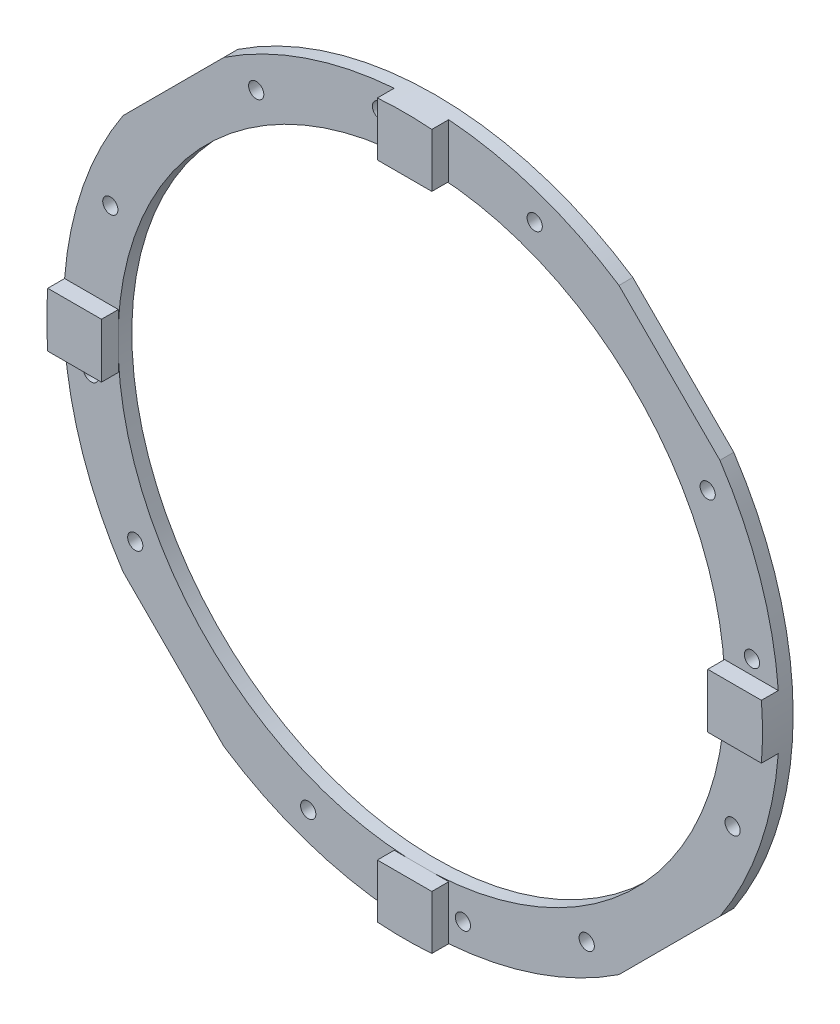
SolidWorks part; units mm, degrees
ref_plane "Front Plane" through (0, 0, 0) normal (0, 0, 1) x (1, 0, 0)
ref_plane "Top Plane" through (0, 0, 0) normal (0, 1, 0) x (1, 0, 0)
ref_plane "Right Plane" through (0, 0, 0) normal (1, 0, 0) x (0, 0, -1)
sketch "Sketch1" plane through (0, 0, 0) normal (0, 0, 1) x (1, 0, 0)
  line L0 (0, 284.5128) -> (0, -315.9314) construction
  line L1 (-464.297, 0) -> (544.589, 0) construction
  circle A2 centre (0, 0) radius 137.5
  circle A3 centre (0, 0) radius 109.75
  dimension "D2" = 275
  dimension "D3" = 219.5
sketch "Sketch2" plane through (0, 0, 0) normal (0, 0, 1) x (1, 0, 0)
  line L1 (0, 193.6178) -> (0, -181.834) construction
  line L2 (0, 284.5128) -> (0, -315.9314) construction
  line L3 (-312.5976, 0) -> (255.9939, 0) construction
  line L4 (-464.297, 0) -> (544.589, 0) construction
  line L5 (-61.2695, 129.5) -> (85.8777, 129.5) construction
  line L6 (-105.1774, 119.5) -> (123.1159, 119.5) construction
  line L7 (0, 0) -> (52.2887, 143.6619) construction
  circle A2 centre (0, 0) radius 109.725
  circle A3 centre (0, 0) radius 129.4
  circle A5 centre (-15, 119.5) radius 2.75
  circle A6 centre (40.9484, 112.5047) radius 2.75
  circle A7 centre (119.5, 15) radius 2.75
  circle A8 centre (112.5047, -40.9484) radius 2.75
  circle A9 centre (15, -119.5) radius 2.75
  circle A10 centre (-40.9484, -112.5047) radius 2.75
  circle A11 centre (-119.5, -15) radius 2.75
  circle A12 centre (-112.5047, 40.9484) radius 2.75
  point P1 (114.75, 0)
  point P3 (0, 0)
  point P9 (104.9544, 32.0878)
  dimension "D1" = 219.45
  dimension "D2" = 258.8
  dimension "D3" = 129.5
  dimension "D5" = 5.5
  dimension "D8" = 5.5
  dimension "D10" = 4
  dimension "D9" = 119.725
  dimension "D4" = 10
  dimension "D6" = 15
  dimension "D7" = 20
extrude "Boss-Extrude1" add sketch "Sketch2" along normal blind 5
sketch "Sketch3" plane through (0, 0, 5) normal (0, 0, 1) x (1, 0, 0)
  line L0 (0, 206.7973) -> (0, -176.6166) construction
  line L2 (-227.1373, 0) -> (214.6054, 0) construction
  line L3 (-464.297, 0) -> (544.589, 0) construction
  line L7 (0, 284.5128) -> (0, -315.9314) construction
  line L18 (-9.85, 129.0246) -> (-9.85, 109.6)
  line L19 (-9.85, 109.6) -> (9.85, 109.6)
  line L20 (9.85, 129.0246) -> (9.85, 109.6)
  line L21 (129.0246, 9.85) -> (109.6, 9.85)
  line L22 (109.6, 9.85) -> (109.6, -9.85)
  line L23 (129.0246, -9.85) -> (109.6, -9.85)
  line L24 (9.85, -129.0246) -> (9.85, -109.6)
  line L25 (9.85, -109.6) -> (-9.85, -109.6)
  line L26 (-9.85, -129.0246) -> (-9.85, -109.6)
  line L27 (-129.0246, -9.85) -> (-109.6, -9.85)
  line L28 (-109.6, -9.85) -> (-109.6, 9.85)
  line L29 (-129.0246, 9.85) -> (-109.6, 9.85)
  arc A8 (9.85, 129.0246) -> (-9.85, 129.0246) centre (0, 0) ccw
  arc A9 (129.0246, -9.85) -> (129.0246, 9.85) centre (0, 0) ccw
  arc A10 (-9.85, -129.0246) -> (9.85, -129.0246) centre (0, 0) ccw
  arc A11 (-129.0246, 9.85) -> (-129.0246, -9.85) centre (0, 0) ccw
  point P14 (0, 109.6)
  dimension "D3" = 109.6
  dimension "D2" = 9.85
  dimension "D1" = 129.4
  dimension "D4" = 4
extrude "Boss-Extrude2" add sketch "Sketch3" along normal blind 6.1
sketch "Sketch4" plane through (0, 0, 0) normal (0, 0, 1) x (1, 0, 0)
  line L0 (0, 353.4924) -> (0, -398.9655) construction
  line L1 (-566.361, 0) -> (629.3551, 0) construction
  line L2 (126.8, 52.5223) -> (52.5223, 126.8)
  line L30 (-53.6407, 129.5) -> (-129.5, 53.6407)
  line L32 (-129.5, -53.6407) -> (-53.6407, -129.5)
  line L34 (53.6407, -129.5) -> (129.5, -53.6407)
  line L36 (129.5, 53.6407) -> (53.6407, 129.5)
  line L38 (-52.5223, 126.8) -> (-126.8, 52.5223)
  line L40 (-126.8, -52.5223) -> (-52.5223, -126.8)
  line L42 (52.5223, -126.8) -> (126.8, -52.5223)
  line L44 (-53.6407, 129.5) -> (-52.5223, 126.8)
  line L45 (53.6407, 129.5) -> (-53.6407, 129.5) construction
  line L46 (52.5223, 126.8) -> (-52.5223, 126.8) construction
  line L47 (53.6407, 129.5) -> (0, 129.5) [skipped]
  line L48 (126.8, -52.5223) -> (126.8, 52.5223) construction
  line L49 (129.5, -53.6407) -> (129.5, 53.6407) construction
  line L50 (129.5, 0) -> (129.5, 53.6407) [skipped]
  line L51 (-52.5223, -126.8) -> (52.5223, -126.8) construction
  line L52 (-53.6407, -129.5) -> (53.6407, -129.5) construction
  line L53 (0, -129.5) -> (53.6407, -129.5) [skipped]
  line L54 (-126.8, 52.5223) -> (-126.8, -52.5223) construction
  line L55 (-129.5, 53.6407) -> (-129.5, -53.6407) construction
  line L56 (-129.5, 53.6407) -> (-129.5, 0) [skipped]
  line L57 (-129.5, 53.6407) -> (-126.8, 52.5223)
  line L58 (53.6407, 129.5) -> (52.5223, 126.8)
  line L59 (129.5, 53.6407) -> (126.8, 52.5223)
  line L60 (126.8, -52.5223) -> (129.5, -53.6407)
  line L61 (52.5223, -126.8) -> (53.6407, -129.5)
  line L62 (-52.5223, -126.8) -> (-53.6407, -129.5)
  line L63 (-126.8, -52.5223) -> (-129.5, -53.6407)
  circle A0 centre (0, 0) radius 129.5 construction
  dimension "D3" = 2.7
extrude "Cut-Extrude3" cut sketch "Sketch4" along normal blind 10
sketch "Sketch5" plane through (0, 0, 0) normal (0, 0, 1) x (1, 0, 0)
  line L0 (0, 0) -> (131.1984, 75.7474) construction
  line L1 (-464.297, 0) -> (544.589, 0) construction
  circle A0 centre (103.49, 59.75) radius 2.75
  circle A1 centre (59.75, -103.49) radius 2.75
  circle A2 centre (-103.49, -59.75) radius 2.75
  circle A3 centre (-59.75, 103.49) radius 2.75
  dimension "D2" = 5.5
  dimension "D3" = 119.5
  dimension "D1" = 30
  dimension "D4" = 4
extrude "Cut-Extrude4" cut sketch "Sketch5" along normal through all
